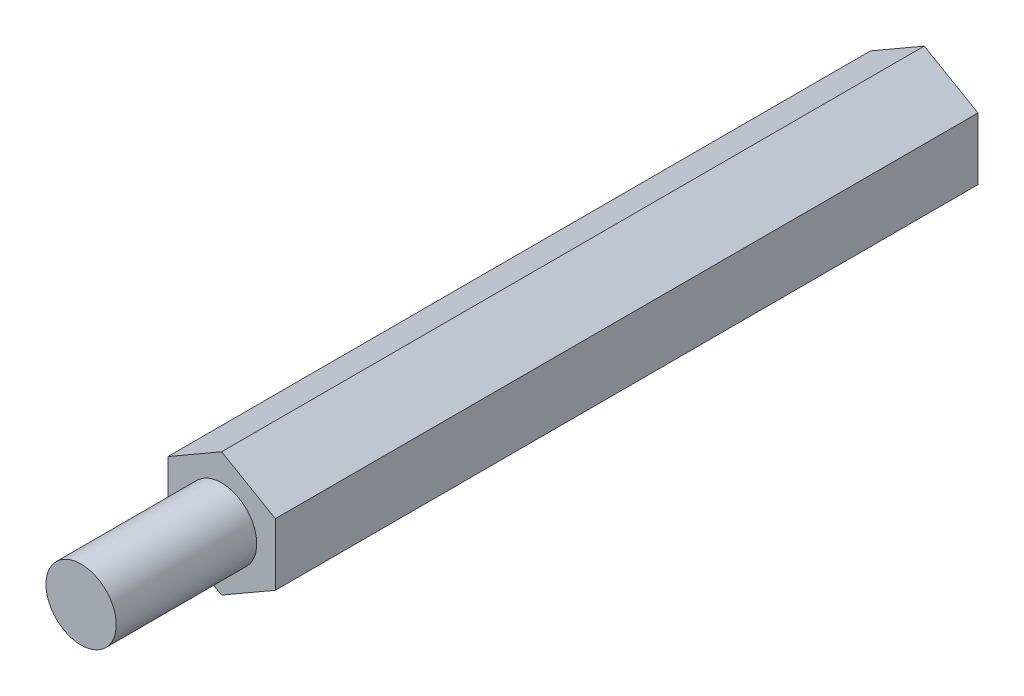
SolidWorks part; units mm, degrees
ref_plane "Front Plane" through (0, 0, 0) normal (0, 0, 1) x (1, 0, 0)
ref_plane "Top Plane" through (0, 0, 0) normal (0, 1, 0) x (1, 0, 0)
ref_plane "Right Plane" through (0, 0, 0) normal (1, 0, 0) x (0, 0, -1)
sketch "Sketch1" plane through (0, 0, 0) normal (0, 0, 1) x (1, 0, 0)
  line L1 (0, 2.65) -> (-2.295, 1.325)
  line L2 (-2.295, 1.325) -> (-2.295, -1.325)
  line L3 (-2.295, -1.325) -> (0, -2.65)
  line L4 (0, -2.65) -> (2.295, -1.325)
  line L5 (2.295, -1.325) -> (2.295, 1.325)
  line L6 (2.295, 1.325) -> (0, 2.65)
  circle A0 centre (0, 0) radius 2.295 construction
  dimension "D1" = 5.3
  dimension "D2" = 2.295
extrude "Boss-Extrude1" add sketch "Sketch1" along normal blind 30
sketch "Sketch2" plane through (0, 0, 0) normal (0, 0, -1) x (-1, 0, 0)
  circle A0 centre (0, 0) radius 1.5
  dimension "D1" = 3
extrude "Cut-Extrude1" cut sketch "Sketch2" against normal blind 6
sketch "Sketch3" plane through (0, 0, 30) normal (0, 0, 1) x (1, 0, 0)
  circle A0 centre (0, 0) radius 1.5
  dimension "D1" = 3
extrude "Boss-Extrude2" add sketch "Sketch3" along normal blind 6
